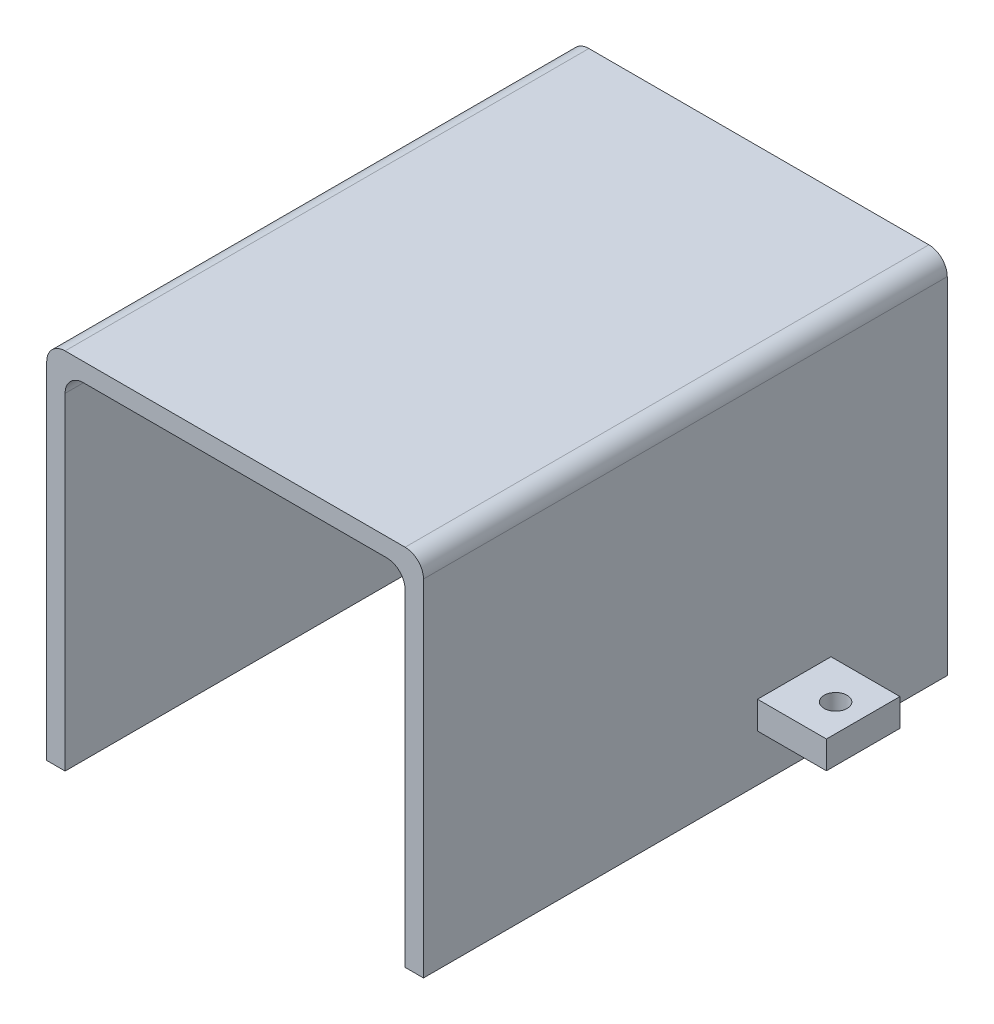
SolidWorks part; units mm, degrees
material "Malleable Cast Iron"
ref_plane "Front Plane" through (0, 0, 0) normal (0, 0, 1) x (1, 0, 0)
ref_plane "Top Plane" through (0, 0, 0) normal (0, 1, 0) x (1, 0, 0)
ref_plane "Right Plane" through (0, 0, 0) normal (1, 0, 0) x (0, 0, -1)
ref_plane "Plane1" through (0, -8.5, 0) normal (0, 1, 0) x (1, 0, 0)
sketch "Sketch1" plane through (0, 0, 0) normal (0, 0, 1) x (1, 0, 0)
  line L0 (-20.5, -13.6) -> (-20.5, 26)
  line L1 (-20.5, 26) -> (20.5, 26)
  line L2 (-18.5, 24) -> (-18.5, -13.6)
  line L3 (-18.5, 24) -> (18.5, 24)
  line L4 (18.5, 24) -> (18.5, -13.6)
  line L5 (20.5, -13.6) -> (20.5, 26)
  line L6 (-20.5, -13.6) -> (-18.5, -13.6)
  line L7 (18.5, -13.6) -> (20.5, -13.6)
  point P0 (0, 0)
  point P10 (0, 24)
  dimension "D1" = 37.6
  dimension "D3" = 37.6
  dimension "D4" = 37
  dimension "D2" = 2
extrude "Boss-Extrude1" add sketch "Sketch1" along normal blind 40.35 and the other way blind 16.65
sketch "Sketch2" plane through (0, -8.5, 0) normal (0, -1, 0) x (-1, 0, 0)
  line L0 (-20.5, -40.35) -> (-20.5, 16.65) construction
  line L1 (-20.5, 4) -> (-28, 4)
  line L2 (-20.5, 4) -> (-20.5, -4)
  line L3 (-20.5, -4) -> (-28, -4)
  line L4 (-28, 4) -> (-28, -4)
  line L5 (0, 25.0251) -> (0, -25.8998) construction
  line L6 (28, 4) -> (28, -4)
  line L7 (20.5, -4) -> (28, -4)
  line L8 (20.5, 4) -> (20.5, -4)
  line L9 (20.5, 4) -> (28, 4)
  circle A0 centre (-25, 0) radius 0.5
  circle A1 centre (25, 0) radius 0.5
  point P6 (-20.5, 0)
  dimension "D3" = 1
  dimension "D1" = 7.5
  dimension "D2" = 8
  dimension "D4" = 3
extrude "Boss-Extrude2" add sketch "Sketch2" against normal blind 3 separate body
fillet "Fillet1" radius 2 4 edges at (-20.5, 26, 11.85) (20.5, 26, 11.85) (18.5, 24, 11.85) (-18.5, 24, 11.85)
sketch "Sketch4" plane through (0, -8.5, 0) normal (0, -1, 0) x (-1, 0, 0)
  point P0 (-25, 0)
  point P1 (25, 0)
hole_wizard "M3x0.5 Tapped Hole1" positions "3DSketch2" profile "Sketch5" tap size "M3x0.5" standard "ANSI Metric"
sketch3d "3DSketch2"
  point P0 (-25, -8.5, 0)
  point P3 (25, -8.5, 0)
sketch "Sketch5" plane through (-25, -8.5, 0) normal (1, 0, 0) x (0, 0, -1)
  line L0 (0, 0) -> (0, 3.7511)
  line L1 (0, 3.7511) -> (1.25, 3)
  line L2 (1.25, 3) -> (1.25, 0)
  line L5 (1.25, 0) -> (0, 0)
  line L10 (0, 3.7511) -> (-1.25, 3) construction
  line L11 (0, -6.35) -> (0, 107.95) construction
  dimension "Tap Drill Dia." = 2.5
  dimension "Tap Drill Depth" = 3
  dimension "Drill Angle" = 118
